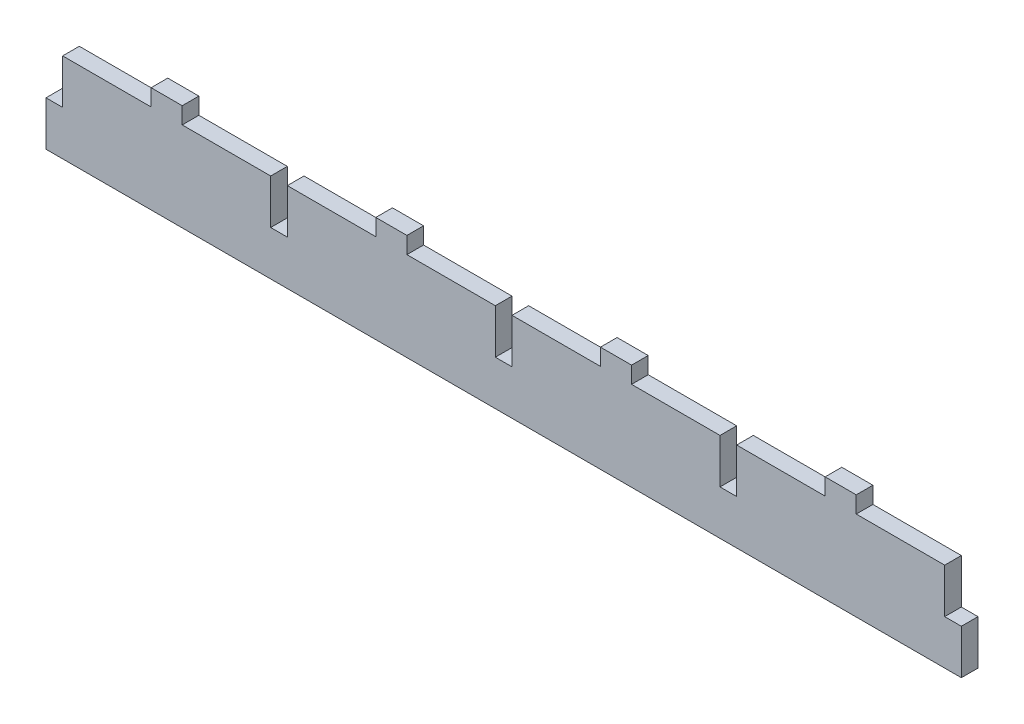
SolidWorks part; units mm, degrees
ref_plane "Front Plane" through (0, 0, 0) normal (0, 0, 1) x (1, 0, 0)
ref_plane "Top Plane" through (0, 0, 0) normal (0, 1, 0) x (1, 0, 0)
ref_plane "Right Plane" through (0, 0, 0) normal (1, 0, 0) x (0, 0, -1)
sketch "Model" plane through (0, 0, 0) normal (0, 0, 1) x (1, 0, 0)
  line L0 (113.2438, 28.65) -> (141.65, 28.65)
  line L1 (-147, 0) -> (147, 0)
  line L2 (-147, 0) -> (-147, 14.32)
  line L3 (-141.65, 28.65) -> (-113.2438, 28.65)
  line L4 (147, 0) -> (147, 14.32)
  line L5 (-147, 14.32) -> (-141.65, 14.32)
  line L8 (-141.65, 14.32) -> (-141.65, 28.65)
  line L9 (147, 14.32) -> (141.65, 14.32)
  line L10 (74.8375, 28.65) -> (103.2437, 28.65)
  line L11 (41.0813, 28.65) -> (69.4875, 28.65)
  line L12 (141.65, 14.32) -> (141.65, 28.65)
  line L13 (2.675, 28.65) -> (31.0812, 28.65)
  line L14 (113.2438, 28.65) -> (113.2438, 34)
  line L15 (113.2438, 34) -> (103.2438, 34)
  line L16 (103.2437, 28.65) -> (103.2438, 34)
  line L18 (-113.2438, 28.65) -> (-113.2438, 34)
  line L19 (-113.2438, 34) -> (-103.2438, 34)
  line L20 (-103.2437, 28.65) -> (-103.2438, 34)
  line L21 (-103.2437, 28.65) -> (-74.8375, 28.65)
  line L22 (-74.8375, 28.65) -> (-74.8375, 14.32)
  line L23 (-74.8375, 14.32) -> (-69.4875, 14.32)
  line L24 (-69.4875, 28.65) -> (-69.4875, 14.32)
  line L25 (-69.4875, 28.65) -> (-41.0812, 28.65)
  line L26 (-41.0812, 28.65) -> (-41.0812, 34)
  line L27 (-41.0812, 34) -> (-31.0813, 34)
  line L28 (-31.0812, 28.65) -> (-31.0813, 34)
  line L29 (-31.0812, 28.65) -> (-2.675, 28.65)
  line L30 (74.8375, 28.65) -> (74.8375, 14.32)
  line L31 (74.8375, 14.32) -> (69.4875, 14.32)
  line L32 (69.4875, 28.65) -> (69.4875, 14.32)
  line L34 (41.0813, 28.65) -> (41.0812, 34)
  line L35 (41.0812, 34) -> (31.0813, 34)
  line L36 (31.0812, 28.65) -> (31.0813, 34)
  line L38 (2.675, 28.65) -> (2.675, 14.32)
  line L39 (2.675, 14.32) -> (-2.675, 14.32)
  line L40 (-2.675, 28.65) -> (-2.675, 14.32)
  dimension "D2" = 5.35
  dimension "D4" = 5.35
  dimension "D6" = 14.33
  dimension "D8" = 294
  dimension "D10" = 28.65
  dimension "D14" = 10
extrude "Boss-Extrude1" add sketch "Model" along normal blind 5.35
equation "\"mdfthick\"=5.35"
equation "\"D2@Model\"=\"mdfthick\""
equation "\"D4@Model\"=\"mdfthick\""
equation "\"D1@Boss-Extrude1\"=\"mdfthick\""
